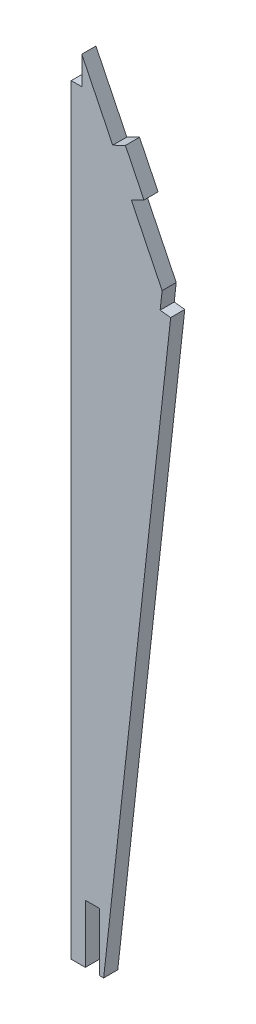
SolidWorks part; units mm, degrees
ref_plane "前视基准面" through (0, 0, 0) normal (0, 0, 1) x (1, 0, 0)
ref_plane "上视基准面" through (0, 0, 0) normal (0, 1, 0) x (1, 0, 0)
ref_plane "右视基准面" through (0, 0, 0) normal (1, 0, 0) x (0, 0, -1)
sketch "草图1" plane through (0, 0, 0) normal (0, 0, 1) x (1, 0, 0)
  line L0 (14.9586, 121.9855) -> (14.9586, 117.9855)
  line L1 (14.9586, 117.9855) -> (13.4586, 117.9855)
  line L2 (13.4586, 117.9855) -> (13.4586, 10.1156)
  line L3 (14.9586, 121.9855) -> (19.3423, 112.9976)
  line L4 (19.3423, 112.9976) -> (21.1399, 113.8743)
  line L5 (21.1399, 113.8743) -> (23.7701, 108.4816)
  line L6 (23.7701, 108.4816) -> (21.9725, 107.6048)
  line L7 (21.9725, 107.6048) -> (26.343, 98.6441)
  line L8 (13.4586, 10.1156) -> (15.4586, 10.1156)
  line L9 (15.4586, 10.1156) -> (15.4586, 18.3656)
  line L10 (15.4586, 18.3656) -> (17.4586, 18.3656)
  line L11 (27.5532, 95.9434) -> (18.0547, 10.1156)
  line L12 (17.4586, 18.3656) -> (17.4586, 10.1156)
  line L13 (17.4586, 10.1156) -> (18.0547, 10.1156)
  line L14 (26.343, 98.6441) -> (26.0623, 96.1084)
  line L15 (26.0623, 96.1084) -> (27.5532, 95.9434)
  line L16 (26.343, 98.6441) -> (26.0623, 96.1084)
  line L17 (26.0623, 96.1084) -> (27.5532, 95.9434)
extrude "凸台-拉伸1" add sketch "草图1" along normal blind 2 contours L15 L14 L7 L6 L5 L4 L3 L0 L1 L2 L8 L9 L10 L12 L13 L11
